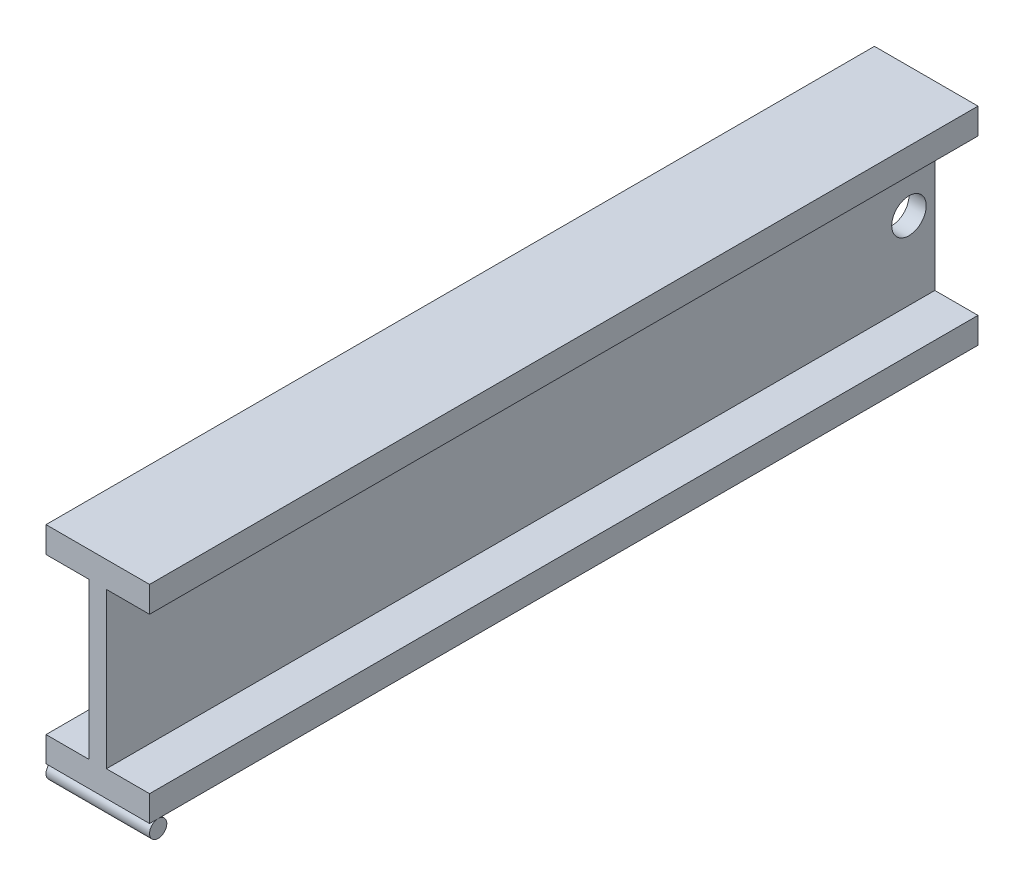
SolidWorks part; units mm, degrees
ref_plane "Front Plane" through (0, 0, 0) normal (0, 0, 1) x (1, 0, 0)
ref_plane "Top Plane" through (0, 0, 0) normal (0, 1, 0) x (1, 0, 0)
ref_plane "Right Plane" through (0, 0, 0) normal (1, 0, 0) x (0, 0, -1)
sketch "Sketch2" plane through (0, 0, 0) normal (0, 0, 1) x (1, 0, 0)
  line L0 (76.2, -152.4) -> (76.2, -114.3)
  line L1 (-76.2, -152.4) -> (76.2, -152.4)
  line L2 (-76.2, -152.4) -> (-76.2, 152.4)
  line L3 (-76.2, 152.4) -> (76.2, 152.4)
  line L4 (76.2, -152.4) -> (76.2, 152.4)
  line L5 (-76.2, -152.4) -> (76.2, 152.4) construction
  line L6 (-76.2, 152.4) -> (76.2, -152.4) construction
  line L7 (76.2, 152.4) -> (76.2, 114.3)
  line L8 (76.2, 114.3) -> (12.7, 114.3)
  line L9 (-76.2, 152.4) -> (-76.2, 114.3)
  line L10 (-76.2, 114.3) -> (-12.7, 114.3)
  line L11 (-76.2, 114.3) -> (-12.7, 114.3)
  line L12 (-76.2, 114.3) -> (-76.2, -115.1682)
  line L13 (-12.7, 114.3) -> (-12.7, -115.1682)
  line L14 (-76.2, -115.1682) -> (-12.7, -115.1682)
  line L15 (76.2, -114.3) -> (76.2, 114.3)
  line L16 (76.2, -114.3) -> (12.7, -114.3)
  line L17 (76.2, 114.3) -> (12.7, 114.3)
  line L18 (12.7, -114.3) -> (12.7, 114.3)
  point P0 (0, 0)
  dimension "D1" = 152.4
  dimension "D2" = 304.8
  dimension "D3" = 38.1
  dimension "D4" = 38.1
  dimension "D5" = 63.5
  dimension "D6" = 63.5
extrude "Boss-Extrude1" add sketch "Sketch2" along normal blind 1219.2 contours L16 L18 L8 L4 L3 L2 L10 L13 L14 L1 L0
sketch "Sketch3" plane through (-12.7, 0, 0) normal (-1, 0, 0) x (0, 0, 1)
  line L0 (0, 152.4) -> (0, 0)
  line L1 (0, 0) -> (38.1, 0)
  circle A0 centre (38.1, 0) radius 25.4
  dimension "D2" = 50.8
  dimension "D1" = 38.1
extrude "Cut-Extrude1" cut sketch "Sketch3" along normal blind 11.43 and the other way blind 41.148
sketch "Sketch4" plane through (-76.2, 0, 0) normal (-1, 0, 0) x (0, 0, 1)
  line L0 (1219.2, -152.4) -> (1219.2, -177.8)
  line L1 (1219.2, -177.8) -> (1193.8, -177.8)
  line L2 (1193.8, -177.8) -> (1193.8, -152.4)
  line L3 (1219.2, -152.4) -> (0, -152.4) construction
  line L4 (1193.8, -152.4) -> (1219.2, -152.4)
  circle A0 centre (1206.5, -165.1) radius 12.7
  dimension "D3" = 25.4
  dimension "D1" = 25.4
  dimension "D2" = 25.4
extrude "Boss-Extrude2" add sketch "Sketch4" against normal blind 152.4 separate body contours A0
